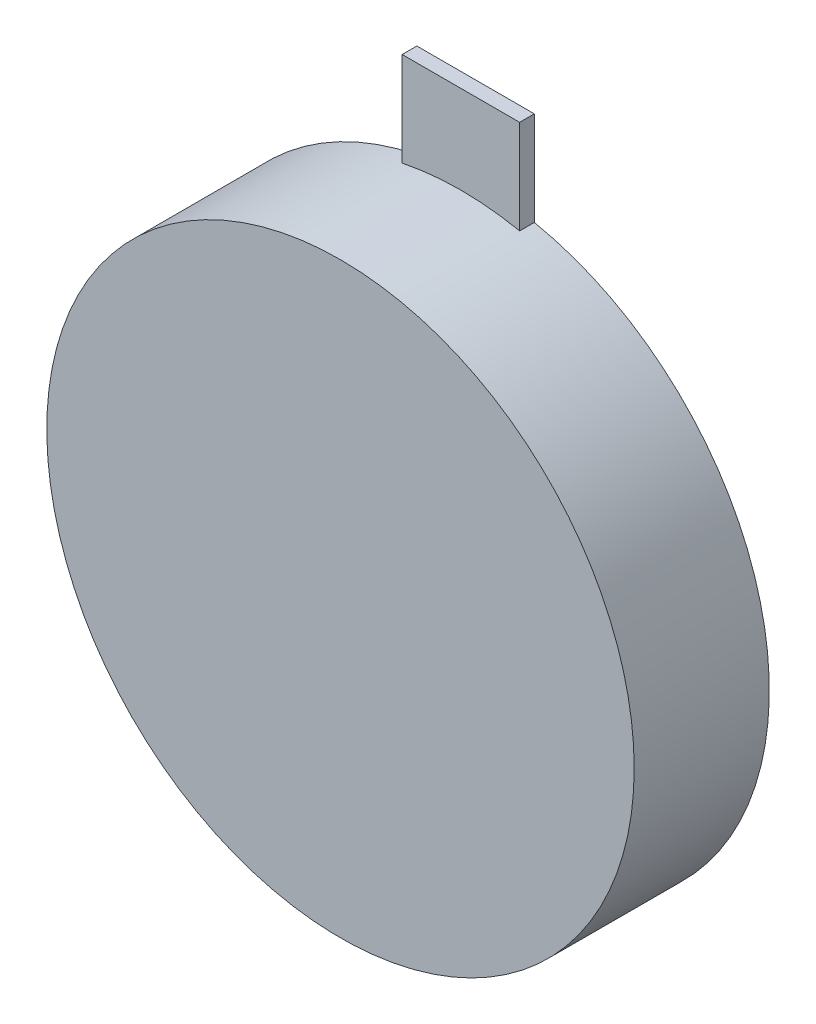
SolidWorks part; units mm, degrees
ref_plane "Front Plane" through (0, 0, 0) normal (0, 0, 1) x (1, 0, 0)
ref_plane "Top Plane" through (0, 0, 0) normal (0, 1, 0) x (1, 0, 0)
ref_plane "Right Plane" through (0, 0, 0) normal (1, 0, 0) x (0, 0, -1)
ref_plane "扬声器背面" through (0, 0, 7.6) normal (0, 0, 1) x (1, 0, 0)
sketch "磁钢凸台_草图" plane through (0, 0, 7.6) normal (0, 0, 1) x (1, 0, 0)
  circle A0 centre (15, -35) radius 7.3
  dimension "D1" = 14.6
extrude "磁钢凸台" add sketch "磁钢凸台_草图" along normal blind 0.5
ref_plane "扬声器框架背面" through (0, 0, 8.1) normal (0, 0, 1) x (1, 0, 0)
sketch "扬声器框架_草图" plane through (0, 0, 8.1) normal (0, 0, 1) x (1, 0, 0)
  circle A0 centre (15, -35) radius 10
  dimension "D1" = 20
extrude "扬声器框架" add sketch "扬声器框架_草图" along normal blind 4.6
sketch "焊片耳朵_草图" plane through (0, 0, 8.1) normal (0, 0, 1) x (1, 0, 0)
  line L1 (13, -26) -> (17, -26)
  line L2 (13, -26) -> (13, -22)
  line L3 (13, -22) -> (17, -22)
  line L4 (17, -26) -> (17, -22)
  dimension "D1" = 4
  dimension "D2" = 4
extrude "焊片耳朵" add sketch "焊片耳朵_草图" along normal blind 0.5
ref_plane "刻字面" through (0, 0, 7.6) normal (0, 0, 1) x (1, 0, 0)
sketch "刻字_喇叭_草图" plane through (0, 0, 7.6) normal (0, 0, 1) x (1, 0, 0)
  line L0 (19.0762, -35.7662) -> (19.0762, -33.7936)
  line L1 (19.0762, -33.7936) -> (18.3128, -33.7936)
  line L2 (18.3128, -33.7936) -> (18.3128, -33.3868)
  line L3 (18.3128, -33.3868) -> (19.1152, -33.3868)
  line L4 (19.1152, -33.3868) -> (19.1152, -32.7292)
  line L5 (19.1152, -32.7292) -> (18.3128, -32.7292)
  line L6 (18.3128, -32.7292) -> (18.3128, -32.25)
  line L7 (18.3128, -32.25) -> (17.75, -32.25)
  line L8 (17.75, -32.25) -> (17.75, -32.7292)
  line L9 (17.75, -32.7292) -> (16.9531, -32.7292)
  line L10 (16.9531, -32.7292) -> (16.9531, -33.3868)
  line L11 (16.9531, -33.3868) -> (17.75, -33.3868)
  line L12 (17.75, -33.3868) -> (17.75, -33.7936)
  line L13 (17.75, -33.7936) -> (16.981, -33.7936)
  line L14 (16.981, -33.7936) -> (16.981, -35.7662)
  line L15 (16.981, -35.7662) -> (17.75, -35.7662)
  line L16 (17.75, -35.7662) -> (17.75, -36.1563)
  line L17 (17.75, -36.1563) -> (17.4268, -35.8777)
  line L18 (17.4268, -35.8777) -> (17.3341, -35.9682)
  line L19 (17.3341, -35.9682) -> (17.2342, -36.069)
  line L20 (17.2342, -36.069) -> (17.1273, -36.18)
  line L21 (17.1273, -36.18) -> (17.0132, -36.3012)
  line L22 (17.0132, -36.3012) -> (16.892, -36.4326)
  line L23 (16.892, -36.4326) -> (16.7637, -36.5742)
  line L24 (16.7637, -36.5742) -> (17.1983, -36.981)
  line L25 (17.1983, -36.981) -> (17.2849, -36.8711)
  line L26 (17.2849, -36.8711) -> (17.3736, -36.7606)
  line L27 (17.3736, -36.7606) -> (17.4644, -36.6494)
  line L28 (17.4644, -36.6494) -> (17.5574, -36.5377)
  line L29 (17.5574, -36.5377) -> (17.6526, -36.4253)
  line L30 (17.6526, -36.4253) -> (17.75, -36.3123)
  line L31 (17.75, -36.3123) -> (17.75, -37.7389)
  line L32 (17.75, -37.7389) -> (18.3128, -37.7389)
  line L33 (18.3128, -37.7389) -> (18.3128, -36.5296)
  line L34 (18.3128, -36.5296) -> (18.4236, -36.7233)
  line L35 (18.4236, -36.7233) -> (18.5407, -36.9104)
  line L36 (18.5407, -36.9104) -> (18.6639, -37.0911)
  line L37 (18.6639, -37.0911) -> (18.7933, -37.2652)
  line L38 (18.7933, -37.2652) -> (18.9289, -37.4328)
  line L39 (18.9289, -37.4328) -> (19.0707, -37.594)
  line L40 (19.0707, -37.594) -> (19.1176, -37.472)
  line L41 (19.1176, -37.472) -> (19.1654, -37.3513)
  line L42 (19.1654, -37.3513) -> (19.2142, -37.2318)
  line L43 (19.2142, -37.2318) -> (19.2638, -37.1135)
  line L44 (19.2638, -37.1135) -> (19.3145, -36.9965)
  line L45 (19.3145, -36.9965) -> (19.366, -36.8807)
  line L46 (19.366, -36.8807) -> (19.2002, -36.729)
  line L47 (19.2002, -36.729) -> (19.0409, -36.5637)
  line L48 (19.0409, -36.5637) -> (18.8882, -36.3848)
  line L49 (18.8882, -36.3848) -> (18.7419, -36.1922)
  line L50 (18.7419, -36.1922) -> (18.6021, -35.986)
  line L51 (18.6021, -35.986) -> (18.4688, -35.7662)
  line L52 (18.4688, -35.7662) -> (19.0762, -35.7662)
  line L53 (19.2601, -32.6401) -> (19.2601, -36.5909)
  line L54 (19.2601, -36.5909) -> (20.0236, -36.5909)
  line L55 (20.0236, -36.5909) -> (20.0236, -37.1537)
  line L56 (20.0236, -37.1537) -> (20.5418, -37.1537)
  line L57 (20.5418, -37.1537) -> (20.5418, -32.6401)
  line L58 (20.5418, -32.6401) -> (19.2601, -32.6401)
  line L59 (16.0003, -32.25) -> (15.4263, -32.25)
  line L60 (15.4263, -32.25) -> (15.4263, -37.02)
  line L61 (15.4263, -37.02) -> (15.4425, -37.2115)
  line L62 (15.4425, -37.2115) -> (15.4913, -37.3698)
  line L63 (15.4913, -37.3698) -> (15.5726, -37.4951)
  line L64 (15.5726, -37.4951) -> (15.6863, -37.5872)
  line L65 (15.6863, -37.5872) -> (15.8326, -37.6461)
  line L66 (15.8326, -37.6461) -> (16.0114, -37.672)
  line L67 (16.0114, -37.672) -> (16.7358, -37.672)
  line L68 (16.7358, -37.672) -> (16.7491, -37.5468)
  line L69 (16.7491, -37.5468) -> (16.7631, -37.4274)
  line L70 (16.7631, -37.4274) -> (16.7776, -37.314)
  line L71 (16.7776, -37.314) -> (16.7928, -37.2064)
  line L72 (16.7928, -37.2064) -> (16.8086, -37.1047)
  line L73 (16.8086, -37.1047) -> (16.825, -37.0089)
  line L74 (16.825, -37.0089) -> (16.7501, -37.0177)
  line L75 (16.7501, -37.0177) -> (16.6702, -37.0256)
  line L76 (16.6702, -37.0256) -> (16.5854, -37.0325)
  line L77 (16.5854, -37.0325) -> (16.4956, -37.0386)
  line L78 (16.4956, -37.0386) -> (16.4008, -37.0437)
  line L79 (16.4008, -37.0437) -> (16.3012, -37.0479)
  line L80 (16.3012, -37.0479) -> (16.2092, -37.0404)
  line L81 (16.2092, -37.0404) -> (16.134, -37.0182)
  line L82 (16.134, -37.0182) -> (16.0755, -36.981)
  line L83 (16.0755, -36.981) -> (16.0337, -36.929)
  line L84 (16.0337, -36.929) -> (16.0086, -36.8621)
  line L85 (16.0086, -36.8621) -> (16.0003, -36.7804)
  line L86 (16.0003, -36.7804) -> (16.0003, -32.25)
  line L87 (16.2677, -36.5073) -> (16.7581, -36.5073)
  line L88 (16.7581, -36.5073) -> (16.7581, -32.785)
  line L89 (16.7581, -32.785) -> (16.2677, -32.785)
  line L90 (16.2677, -32.785) -> (16.2677, -36.5073)
  line L91 (20.0236, -33.2698) -> (20.0236, -35.9612)
  line L92 (20.0236, -35.9612) -> (19.7561, -35.9612)
  line L93 (19.7561, -35.9612) -> (19.7561, -33.2698)
  line L94 (19.7561, -33.2698) -> (20.0236, -33.2698)
  line L95 (17.4825, -35.1755) -> (17.4825, -34.3842)
  line L96 (17.4825, -34.3842) -> (17.75, -34.3842)
  line L97 (17.75, -34.3842) -> (17.75, -35.1755)
  line L98 (17.75, -35.1755) -> (17.4825, -35.1755)
  line L99 (18.5747, -35.1755) -> (18.3128, -35.1755)
  line L100 (18.3128, -35.1755) -> (18.3128, -34.3842)
  line L101 (18.3128, -34.3842) -> (18.5747, -34.3842)
  line L102 (18.5747, -34.3842) -> (18.5747, -35.1755)
  line L103 (14.8356, -32.5955) -> (13.1026, -32.5955)
  line L104 (13.1026, -32.5955) -> (13.1026, -36.3235)
  line L105 (13.1026, -36.3235) -> (12.9161, -35.8781)
  line L106 (12.9161, -35.8781) -> (12.7651, -35.3557)
  line L107 (12.7651, -35.3557) -> (12.6498, -34.7562)
  line L108 (12.6498, -34.7562) -> (12.5701, -34.0796)
  line L109 (12.5701, -34.0796) -> (12.526, -33.3259)
  line L110 (12.526, -33.3259) -> (12.5175, -32.4952)
  line L111 (12.5175, -32.4952) -> (11.8042, -32.5565)
  line L112 (11.8042, -32.5565) -> (11.8042, -33.0843)
  line L113 (11.8042, -33.0843) -> (11.8153, -33.5831)
  line L114 (11.8153, -33.5831) -> (11.8376, -34.0527)
  line L115 (11.8376, -34.0527) -> (11.8711, -34.4932)
  line L116 (11.8711, -34.4932) -> (11.9157, -34.9046)
  line L117 (11.9157, -34.9046) -> (11.9714, -35.287)
  line L118 (11.9714, -35.287) -> (12.0658, -35.7439)
  line L119 (12.0658, -35.7439) -> (12.1893, -36.1823)
  line L120 (12.1893, -36.1823) -> (12.3419, -36.6021)
  line L121 (12.3419, -36.6021) -> (12.5237, -37.0033)
  line L122 (12.5237, -37.0033) -> (12.7345, -37.3859)
  line L123 (12.7345, -37.3859) -> (12.9744, -37.75)
  line L124 (12.9744, -37.75) -> (13.0393, -37.6717)
  line L125 (13.0393, -37.6717) -> (13.1187, -37.5816)
  line L126 (13.1187, -37.5816) -> (13.2126, -37.4797)
  line L127 (13.2126, -37.4797) -> (13.3211, -37.3661)
  line L128 (13.3211, -37.3661) -> (13.4442, -37.2407)
  line L129 (13.4442, -37.2407) -> (13.5818, -37.1036)
  line L130 (13.5818, -37.1036) -> (13.5001, -36.9912)
  line L131 (13.5001, -36.9912) -> (13.4221, -36.877)
  line L132 (13.4221, -36.877) -> (13.3478, -36.7609)
  line L133 (13.3478, -36.7609) -> (13.2772, -36.6429)
  line L134 (13.2772, -36.6429) -> (13.2103, -36.5231)
  line L135 (13.2103, -36.5231) -> (13.1472, -36.4015)
  line L136 (13.1472, -36.4015) -> (14.1558, -36.4015)
  line L137 (14.1558, -36.4015) -> (14.1558, -36.7525)
  line L138 (14.1558, -36.7525) -> (14.8356, -36.7525)
  line L139 (14.8356, -36.7525) -> (14.8356, -32.5955)
  line L140 (10.5114, -32.3447) -> (10.4945, -33.3125)
  line L141 (10.4945, -33.3125) -> (10.4142, -34.1948)
  line L142 (10.4142, -34.1948) -> (10.2704, -34.9916)
  line L143 (10.2704, -34.9916) -> (10.0631, -35.7031)
  line L144 (10.0631, -35.7031) -> (9.7924, -36.329)
  line L145 (9.7924, -36.329) -> (9.4582, -36.8696)
  line L146 (9.4582, -36.8696) -> (9.5484, -36.996)
  line L147 (9.5484, -36.996) -> (9.6409, -37.1265)
  line L148 (9.6409, -37.1265) -> (9.7354, -37.261)
  line L149 (9.7354, -37.261) -> (9.8322, -37.3996)
  line L150 (9.8322, -37.3996) -> (9.9311, -37.5421)
  line L151 (9.9311, -37.5421) -> (10.0322, -37.6887)
  line L152 (10.0322, -37.6887) -> (10.4074, -37.042)
  line L153 (10.4074, -37.042) -> (10.712, -36.3018)
  line L154 (10.712, -36.3018) -> (10.946, -35.4681)
  line L155 (10.946, -35.4681) -> (11.1095, -34.5409)
  line L156 (11.1095, -34.5409) -> (11.2024, -33.5202)
  line L157 (11.2024, -33.5202) -> (11.2247, -32.406)
  line L158 (11.2247, -32.406) -> (10.5114, -32.3447)
  line L159 (13.7824, -35.7941) -> (13.7824, -33.2029)
  line L160 (13.7824, -33.2029) -> (14.1558, -33.2029)
  line L161 (14.1558, -33.2029) -> (14.1558, -35.7941)
  line L162 (14.1558, -35.7941) -> (13.7824, -35.7941)
extrude "刻字_喇叭" cut sketch "刻字_喇叭_草图" along normal blind 0.3
